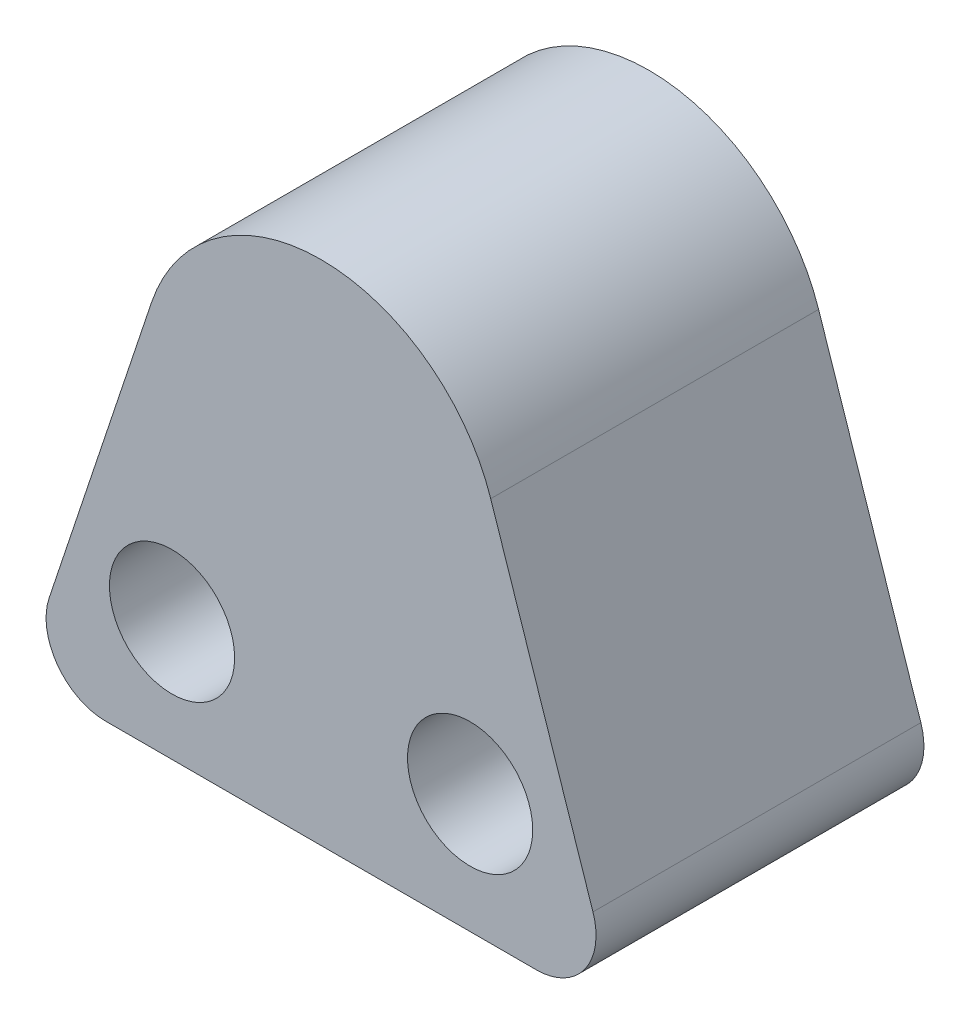
SolidWorks part; units mm, degrees
material "ﾁｰｸ材"
ref_plane "正面" through (0, 0, 0) normal (0, 0, 1) x (1, 0, 0)
ref_plane "平面" through (0, 0, 0) normal (0, 1, 0) x (1, 0, 0)
ref_plane "右側面" through (0, 0, 0) normal (1, 0, 0) x (0, 0, -1)
sketch "ｽｹｯﾁ1" plane through (0, 0, 0) normal (0, 0, 1) x (1, 0, 0)
  line L0 (-5, 0) -> (5, 0)
  line L1 (-5, 0) -> (0, 15)
  line L2 (0, 15) -> (5, 0)
  point P3 (0, 0)
  point P5 (0, 7.4295)
  dimension "D1" = 10
  dimension "D2" = 15
extrude "ﾎﾞｽ - 押し出し1" add sketch "ｽｹｯﾁ1" along normal blind 5.5
fillet "ﾌｨﾚｯﾄ1" radius 1 2 edges at (5, 0, 2.75) (-5, 0, 2.75)
sketch "ｽｹｯﾁ2" plane through (0, 0, 5.5) normal (0, 0, 1) x (1, 0, 0)
  line L0 (-3.6126, 0) -> (3.6126, 0) construction
  circle A0 centre (-2.5, 2) radius 1.05
  circle A1 centre (2.5, 2) radius 1.05
  dimension "D1" = 2.1
  dimension "D2" = 2.1
  dimension "D3" = 2
  dimension "D4" = 2
  dimension "D5" = 2.5
  dimension "D6" = 2.5
extrude "ｶｯﾄ - 押し出し1" cut sketch "ｽｹｯﾁ2" against normal through all
fillet "ﾌｨﾚｯﾄ2" radius 3 1 edges at (0, 15, 2.75)
